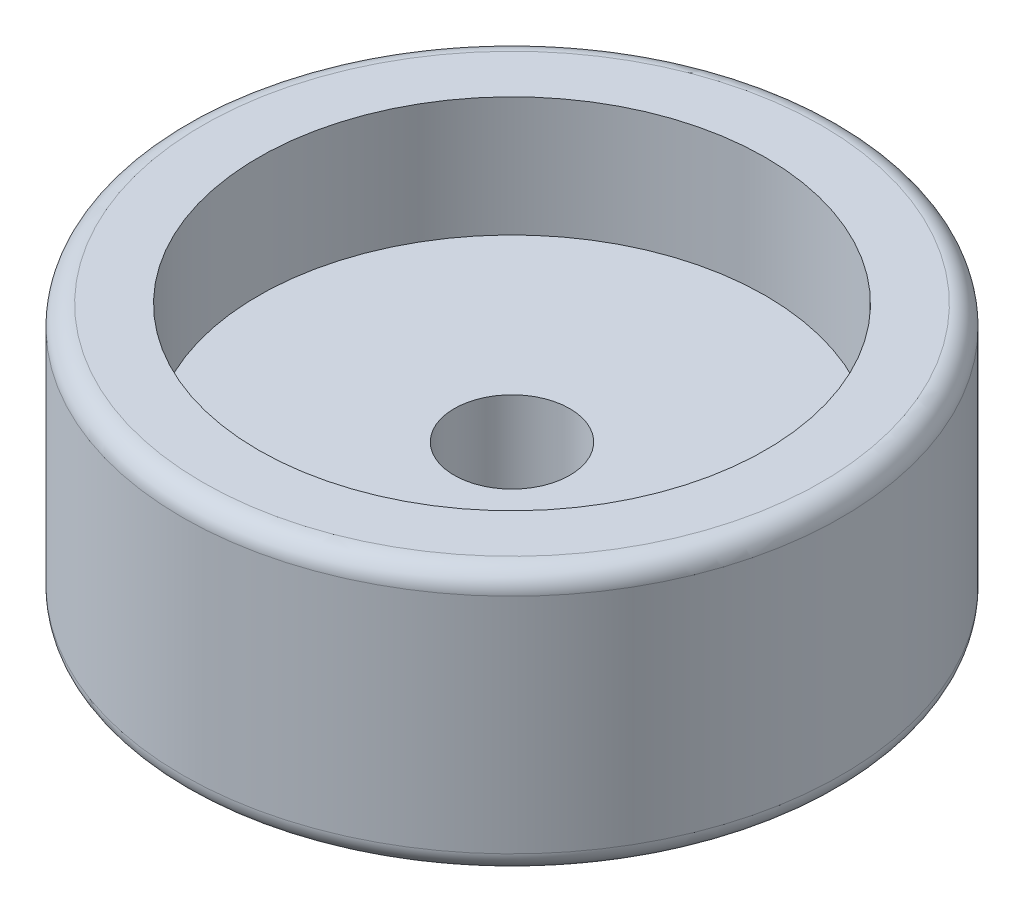
SolidWorks part; units mm, degrees
ref_plane "前视基准面" through (0, 0, 0) normal (0, 0, 1) x (1, 0, 0)
ref_plane "上视基准面" through (0, 0, 0) normal (0, 1, 0) x (1, 0, 0)
ref_plane "右视基准面" through (0, 0, 0) normal (1, 0, 0) x (0, 0, -1)
sketch "草图1" plane through (0, 0, 0) normal (0, 1, 0) x (1, 0, 0)
  circle A0 centre (0, 0) radius 32.5
  circle A1 centre (0, 0) radius 5.7
  dimension "D1" = 65
  dimension "D2" = 11.4
extrude "凸台-拉伸1" add sketch "草图1" along normal blind 26
sketch "草图2" plane through (0, 26, 0) normal (0, 1, 0) x (1, 0, 0)
  circle A0 centre (0, 0) radius 25
  dimension "D1" = 50
extrude "切除-拉伸1" cut sketch "草图2" against normal blind 11.8
fillet "圆角1" radius 2 2 edges at (0, 26, 32.5) (0, 0, 32.5)
